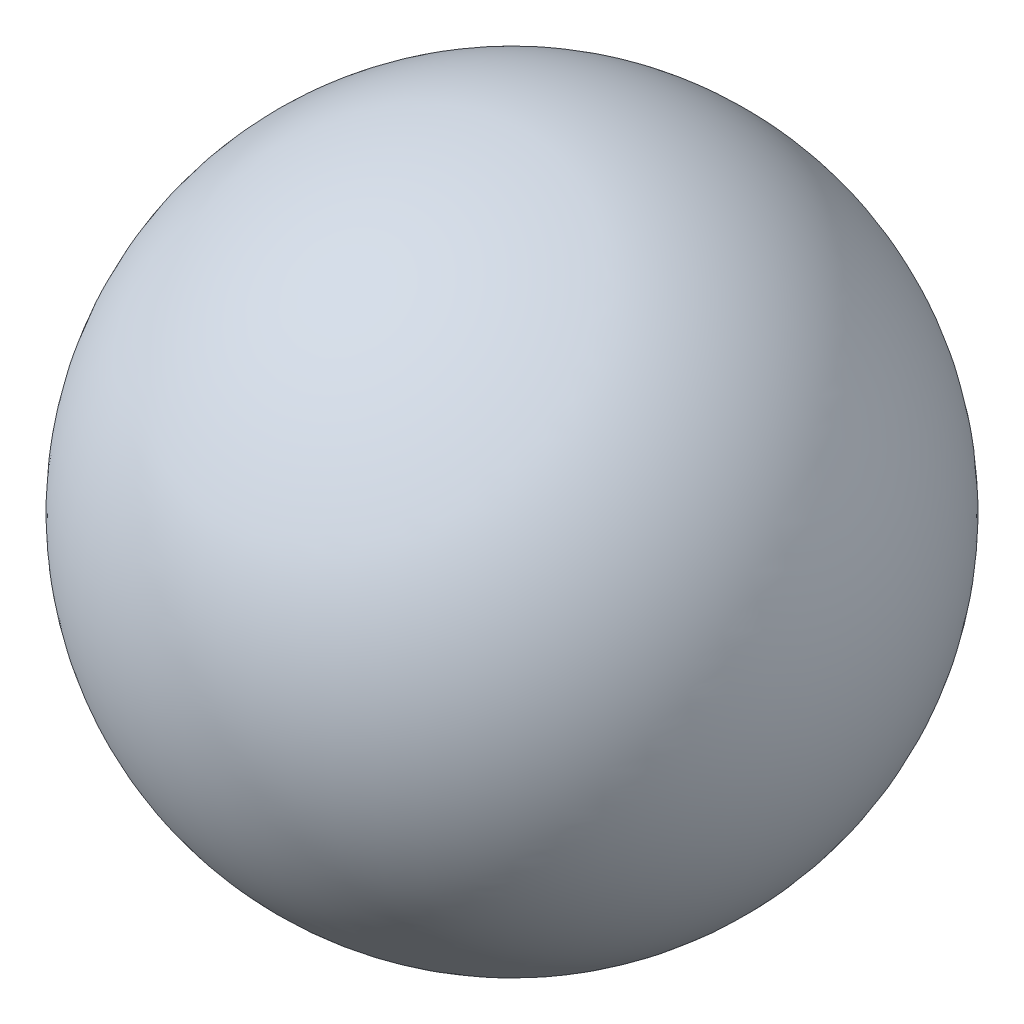
SolidWorks part; units mm, degrees
ref_plane "Front Plane" through (0, 0, 0) normal (0, 0, 1) x (1, 0, 0)
ref_plane "Top Plane" through (0, 0, 0) normal (0, 1, 0) x (1, 0, 0)
ref_plane "Right Plane" through (0, 0, 0) normal (1, 0, 0) x (0, 0, -1)
sketch "Sketch1" plane through (0, 0, 0) normal (0, 0, 1) x (1, 0, 0)
  line L0 (0, 282.0948) -> (0, -282.0948) construction
  line L1 (0, -282.0948) -> (0, 282.0948)
  spline S0 degree 4 poles (-86.3288, -268.5606) (-85.0157, -268.9827) (-78.4366, -271.0503) (-67.8033, -274.0151) (-55.6955, -276.7194) (-43.486, -278.786) (-35.3353, -279.8951) (-29.9215, -280.5255) (-25.1746, -280.9855) (-21.1001, -281.3142) (-17.7015, -281.5444) (-14.981, -281.7022) (-12.5994, -281.8173) (-10.5571, -281.8996) (-8.855, -281.9571) (-7.4939, -281.9966) (-6.1288, -282.0295) (-4.9354, -282.0526) (-3.9296, -282.0682) (-3.0788, -282.0785) (-2.3735, -282.0851) (-1.6388, -282.09) (-0.9096, -282.0933) (-0.1173, -282.0953) (0.6219, -282.0946) (1.9702, -282.0891) (3.3219, -282.0768) (4.6126, -282.0583) (5.9314, -282.0337) (7.5838, -281.9951) (9.5588, -281.9366) (11.8662, -281.8503) (14.5004, -281.727) (17.1341, -281.5791) (19.7659, -281.4066) (22.3963, -281.2095) (25.6816, -280.9324) (29.6197, -280.5507) (34.2067, -280.0339) (40.7446, -279.1731) (53.7745, -277.1261) (70.5522, -273.5165) (90.8211, -267.5396) (112.939, -258.859) (131.9678, -249.6952) (150.2585, -239.1351) (167.709, -227.2376) (184.2215, -214.0693) (199.7038, -199.7038) (214.0693, -184.2215) (227.2376, -167.709) (239.1351, -150.2585) (249.6952, -131.9678) (261.1499, -108.1819) (270.1919, -83.3432) (276.7132, -57.7269) (280.648, -31.6214) (282.2263, -10.5602) (282.2263, 10.5602) (280.648, 31.6214) (277.5002, 52.5059) (272.8005, 73.0967) (266.5751, 93.2787) (258.859, 112.939) (249.6952, 131.9678) (239.1351, 150.2585) (227.2376, 167.709) (214.0693, 184.2215) (199.7038, 199.7038) (184.2215, 214.0693) (167.709, 227.2376) (150.2585, 239.1351) (131.9678, 249.6952) (112.939, 258.859) (93.2787, 266.5751) (73.0967, 272.8005) (56.3666, 276.619) (43.3598, 278.8288) (34.2067, 280.0339) (29.6197, 280.5507) (25.6816, 280.9324) (22.3963, 281.2095) (19.766, 281.4066) (17.1341, 281.5791) (14.5005, 281.727) (12.1953, 281.8349) (10.2183, 281.9119) (8.5711, 281.9658) (7.2535, 282.0028) (5.7658, 282.0375) (4.4485, 282.0611) (3.3239, 282.0764) (2.2932, 282.0857) (1.4006, 282.0915) (0.4992, 282.0947) (-0.117, 282.0953) (-0.9097, 282.0933) (-1.6389, 282.09) (-2.3735, 282.0851) (-3.0788, 282.0785) (-3.9296, 282.0682) (-4.9353, 282.0526) (-6.1288, 282.0295) (-7.4939, 281.9966) (-8.855, 281.9571) (-10.2166, 281.9111) (-11.5783, 281.8585) (-13.2798, 281.7844) (-15.3211, 281.6825) (-17.7015, 281.5444) (-22.4595, 281.2221) (-30.6213, 280.5107) (-42.187, 279.0876) (-55.7124, 276.7063) (-67.7814, 273.9278) (-77.0995, 271.3952) (-82.3841, 269.8098) (-85.0157, 268.9827) (-86.3288, 268.5606) knots 0 0 0 0 0 0.005196 0.025982 0.041571 0.046704 0.051838 0.056971 0.062104 0.064671 0.067238 0.069804 0.072371 0.073654 0.074938 0.076221 0.077504 0.078788 0.079429 0.080071 0.080713 0.081354 0.081996 0.082638 0.08388 0.085122 0.086364 0.087606 0.088848 0.090091 0.092575 0.095059 0.097544 0.100028 0.102512 0.104996 0.107481 0.112449 0.117418 0.122387 0.132324 0.162135 0.18201 0.201884 0.221758 0.241633 0.261507 0.281382 0.301256 0.32113 0.341005 0.360879 0.380754 0.400628 0.440377 0.460251 0.480126 0.5 0.519874 0.539749 0.559623 0.579498 0.599372 0.619246 0.639121 0.658995 0.67887 0.698744 0.718618 0.738493 0.758367 0.778242 0.798116 0.81799 0.837865 0.857739 0.877613 0.882582 0.887551 0.892519 0.895004 0.897488 0.899972 0.902456 0.904941 0.907425 0.908667 0.909909 0.911152 0.912394 0.914257 0.914878 0.915499 0.91612 0.917362 0.918004 0.918646 0.919287 0.919929 0.920571 0.921212 0.922496 0.923779 0.925062 0.926346 0.927629 0.928912 0.930196 0.932762 0.935329 0.937896 0.948162 0.963626 0.979215 0.989607 0.994804 1 1 1 1 1 construction
  spline S1 degree 4 poles (0, -282.0948) (0.2752, -282.0948) (0.82, -282.0938) (1.9702, -282.0891) (3.3219, -282.0768) (4.6126, -282.0583) (5.9314, -282.0337) (7.5838, -281.9951) (9.5588, -281.9366) (11.8662, -281.8503) (14.5004, -281.727) (17.1341, -281.5791) (19.7659, -281.4066) (22.3963, -281.2095) (25.6816, -280.9324) (29.6197, -280.5507) (34.2067, -280.0339) (40.7446, -279.1731) (53.7745, -277.1261) (70.5522, -273.5165) (90.8211, -267.5396) (112.939, -258.859) (131.9678, -249.6952) (150.2585, -239.1351) (167.709, -227.2376) (184.2215, -214.0693) (199.7038, -199.7038) (214.0693, -184.2215) (227.2376, -167.709) (239.1351, -150.2585) (249.6952, -131.9678) (261.1499, -108.1819) (270.1919, -83.3432) (276.7132, -57.7269) (280.648, -31.6214) (282.2263, -10.5602) (282.2263, 10.5602) (280.648, 31.6214) (277.5002, 52.5059) (272.8005, 73.0967) (266.5751, 93.2787) (258.859, 112.939) (249.6952, 131.9678) (239.1351, 150.2585) (227.2376, 167.709) (214.0693, 184.2215) (199.7038, 199.7038) (184.2215, 214.0693) (167.709, 227.2376) (150.2585, 239.1351) (131.9678, 249.6952) (112.939, 258.859) (93.2787, 266.5751) (73.0967, 272.8005) (56.3666, 276.619) (43.3598, 278.8288) (34.2067, 280.0339) (29.6197, 280.5507) (25.6816, 280.9324) (22.3963, 281.2095) (19.766, 281.4066) (17.1341, 281.5791) (14.5005, 281.727) (12.1953, 281.8349) (10.2183, 281.9119) (8.5711, 281.9658) (7.2535, 282.0028) (5.7658, 282.0375) (4.4485, 282.0611) (3.3239, 282.0764) (2.2932, 282.0857) (1.4006, 282.0915) (0.6842, 282.094) (0.2752, 282.0948) (0, 282.0948) knots 0.082638 0.082638 0.082638 0.082638 0.082638 0.08388 0.085122 0.086364 0.087606 0.088848 0.090091 0.092575 0.095059 0.097544 0.100028 0.102512 0.104996 0.107481 0.112449 0.117418 0.122387 0.132324 0.162135 0.18201 0.201884 0.221758 0.241633 0.261507 0.281382 0.301256 0.32113 0.341005 0.360879 0.380754 0.400628 0.440377 0.460251 0.480126 0.5 0.519874 0.539749 0.559623 0.579498 0.599372 0.619246 0.639121 0.658995 0.67887 0.698744 0.718618 0.738493 0.758367 0.778242 0.798116 0.81799 0.837865 0.857739 0.877613 0.882582 0.887551 0.892519 0.895004 0.897488 0.899972 0.902456 0.904941 0.907425 0.908667 0.909909 0.911152 0.912394 0.914257 0.914878 0.915499 0.91612 0.917362 0.917362 0.917362 0.917362 0.917362
revolve "Revolve1" add sketch "Sketch1" angle 360 about L0
